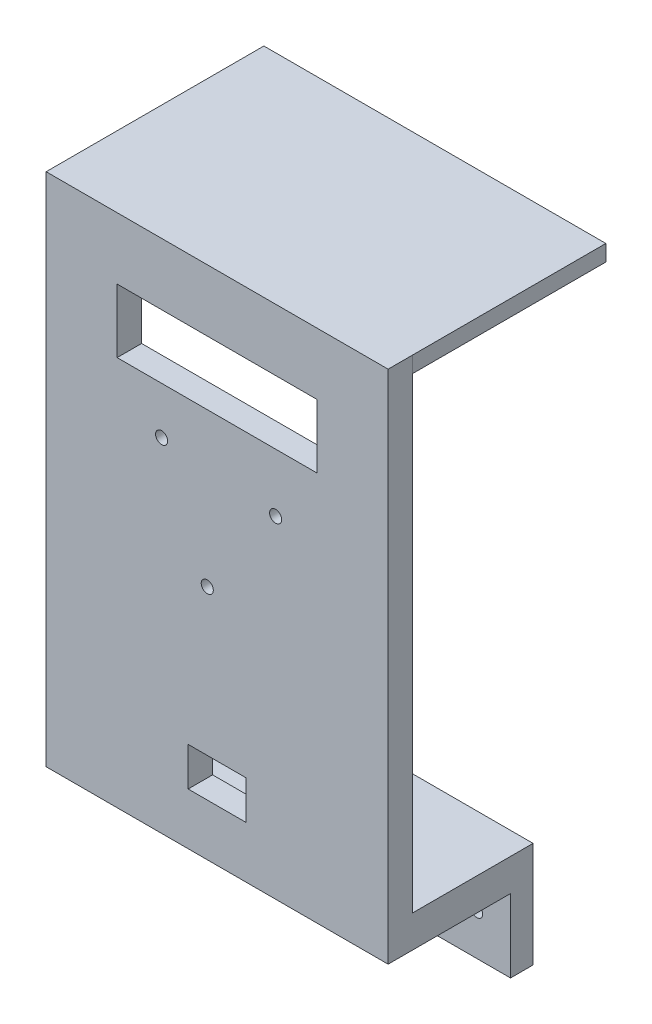
SolidWorks part; units mm, degrees
ref_plane "정면" through (0, 0, 0) normal (0, 0, 1) x (1, 0, 0)
ref_plane "윗면" through (0, 0, 0) normal (0, 1, 0) x (1, 0, 0)
ref_plane "우측면" through (0, 0, 0) normal (1, 0, 0) x (0, 0, -1)
sketch "스케치1" plane through (0, 0, 0) normal (0, 0, 1) x (1, 0, 0)
  line L0 (0, 31.6653) -> (0, -34.8319) construction
  line L1 (-49.7332, 0) -> (50.292, 0) construction
  line L3 (-49.7332, 31.7122) -> (56.4388, 31.7122)
  line L4 (-49.7332, 31.7122) -> (-49.7332, -0.9878)
  line L5 (-49.7332, -0.9878) -> (56.4388, -0.9878)
  line L6 (56.4388, 31.7122) -> (56.4388, -0.9878)
  circle A0 centre (46.0248, 11.8122) radius 1.778
  circle A1 centre (34.8488, 11.8122) radius 1.778
  circle A2 centre (-38.7332, 12.0122) radius 1.778
  circle A3 centre (-27.5332, 12.0122) radius 1.778
  dimension "D7" = 3.556
  dimension "D8" = 3.556
  dimension "D9" = 3.556
  dimension "D10" = 3.556
  dimension "D1" = 106.172
  dimension "D2" = 32.7
  dimension "D3" = 10.414
  dimension "D4" = 11.176
  dimension "D5" = 11
  dimension "D6" = 11.2
  dimension "D11" = 13
  dimension "D12" = 12.8
  dimension "D13" = 12.8
  dimension "D14" = 13
extrude "보스-돌출1" add sketch "스케치1" along normal blind 15
sketch "스케치2" plane through (0, 0, 15) normal (0, 0, 1) x (1, 0, 0)
  line L0 (56.4388, -0.9878) -> (56.4388, 31.7122) construction
  line L1 (56.4388, 31.7122) -> (-49.7332, 31.7122)
  line L2 (56.4388, 31.7122) -> (56.4388, -0.9878)
  line L3 (56.4388, -0.9878) -> (-49.7332, -0.9878)
  line L4 (-49.7332, 31.7122) -> (-49.7332, -0.9878)
  line L5 (-49.7332, 31.7122) -> (-49.7332, -0.9878) construction
  line L6 (-49.7332, -0.9878) -> (56.4388, -0.9878) construction
  circle A0 centre (-38.7332, 12.0122) radius 1.778
  circle A1 centre (-27.5332, 12.0122) radius 1.778
  circle A2 centre (34.8488, 11.8122) radius 1.778
  circle A3 centre (46.0248, 11.8122) radius 1.778
extrude "보스-돌출2" add sketch "스케치2" along normal blind 30
sketch "스케치4" plane through (-49.7332, 0, 0) normal (-1, 0, 0) x (0, 0, 1)
  line L0 (45, -0.9878) -> (25.5028, 31.7122)
  line L1 (45, 31.7122) -> (45, -0.9878) construction
  line L2 (45, 31.7122) -> (25.5028, 31.7122)
  line L3 (45, 31.7122) -> (45, -0.9878)
extrude "보스-돌출3" add sketch "스케치4" against normal blind 106
sketch "스케치6" plane through (0, 31.7122, 0) normal (0, 1, 0) x (1, 0, 0)
sketch "스케치8" plane through (0, 31.7122, 0) normal (0, 1, 0) x (1, 0, 0)
  line L0 (-49.7332, -45) -> (-49.7332, 0) construction
  line L1 (56.4388, -45) -> (-49.7332, -45)
  line L2 (56.4388, -45) -> (56.4388, -37.402)
  line L3 (56.4388, -37.402) -> (-49.7332, -37.402)
  line L4 (-49.7332, -45) -> (-49.7332, -37.402)
extrude "보스-돌출5" add sketch "스케치8" along normal blind 140
sketch "스케치9" plane through (-49.7332, 0, 0) normal (-1, 0, 0) x (0, 0, 1)
  line L0 (45, -0.9878) -> (17.0512, -0.9878)
  line L1 (17.0512, -0.9878) -> (45, 21.7218)
  line L2 (45, 171.7122) -> (45, -0.9878) construction
  line L3 (45, 21.7218) -> (45, -0.9878)
extrude "컷-돌출1" cut sketch "스케치9" against normal blind 146
sketch "스케치10" plane through (0, 0, 37.402) normal (0, 0, -1) x (-1, 0, 0)
  line L0 (49.7332, 171.7122) -> (49.7332, 31.7122) construction
  line L1 (-56.4388, 171.7122) -> (49.7332, 171.7122)
  line L2 (-56.4388, 171.7122) -> (-56.4388, 169.9692)
  line L3 (-56.4388, 169.9692) -> (49.7332, 169.9692)
  line L4 (49.7332, 171.7122) -> (49.7332, 169.9692)
sketch "스케치11" plane through (0, 171.7122, 0) normal (0, 1, 0) x (1, 0, 0)
  line L1 (56.4388, -45) -> (-49.7332, -45)
  line L2 (56.4388, -45) -> (56.4388, -37.402)
  line L3 (56.4388, -37.402) -> (-49.7332, -37.402)
  line L4 (-49.7332, -45) -> (-49.7332, -37.402)
extrude "보스-돌출7" add sketch "스케치11" along normal blind 10
sketch "스케치12" plane through (0, 0, 37.402) normal (0, 0, -1) x (-1, 0, 0)
  line L1 (49.7332, 181.7122) -> (-56.4388, 181.7122)
  line L2 (49.7332, 181.7122) -> (49.7332, 169.9692)
  line L3 (49.7332, 169.9692) -> (-56.4388, 169.9692)
  line L4 (-56.4388, 181.7122) -> (-56.4388, 169.9692)
sketch "스케치13" plane through (0, 0, 37.402) normal (0, 0, -1) x (-1, 0, 0)
  line L1 (-56.4388, 181.7122) -> (49.7332, 181.7122)
  line L2 (-56.4388, 181.7122) -> (-56.4388, 174.0177)
  line L3 (-56.4388, 174.0177) -> (49.7332, 174.0177)
  line L4 (49.7332, 181.7122) -> (49.7332, 174.0177)
sketch "스케치14" plane through (0, 0, 37.402) normal (0, 0, -1) x (-1, 0, 0)
  line L0 (-56.4388, 181.7122) -> (-56.4388, 31.7122) construction
  line L1 (49.7332, 181.7122) -> (-56.4388, 181.7122)
  line L2 (49.7332, 181.7122) -> (49.7332, 164.2058)
  line L3 (49.7332, 164.2058) -> (-56.4388, 164.2058)
  line L4 (-56.4388, 181.7122) -> (-56.4388, 164.2058)
sketch "스케치15" plane through (0, 0, 37.402) normal (0, 0, -1) x (-1, 0, 0)
  line L1 (49.7332, 181.7122) -> (-56.4377, 181.7122)
  line L2 (49.7332, 181.7122) -> (49.7332, 176.7122)
  line L3 (49.7332, 176.7122) -> (-56.4377, 176.7122)
  line L4 (-56.4377, 181.7122) -> (-56.4377, 176.7122)
  dimension "D1" = 5
extrude "보스-돌출11" add sketch "스케치15" along normal blind 60
sketch "스케치16" plane through (0, 0, 45) normal (0, 0, 1) x (1, 0, 0)
  line L0 (-49.7332, 44.5204) -> (56.4388, 44.5204) construction
  line L1 (12.3528, 49.7841) -> (-5.6472, 49.7841)
  line L2 (12.3528, 49.7841) -> (12.3528, 37.7841)
  line L3 (12.3528, 37.7841) -> (-5.6472, 37.7841)
  line L4 (-5.6472, 49.7841) -> (-5.6472, 37.7841)
  line L5 (-49.7332, 181.7122) -> (-49.7332, 21.7218) construction
  line L6 (56.4388, 21.7218) -> (56.4388, 181.7122) construction
  line L7 (3.3528, 49.7841) -> (3.3528, 37.7841) construction
  dimension "D1" = 12
  dimension "D2" = 18
extrude "컷-돌출2" cut sketch "스케치16" against normal blind 7.8
sketch "스케치18" plane through (0, 0, 45) normal (0, 0, 1) x (1, 0, 0)
  circle A1 centre (-13.8821, 128.1414) radius 1.875
  circle A3 centre (21.5155, 124.7012) radius 1.875
  circle A4 centre (0.2881, 95.1274) radius 1.875
  dimension "D2" = 3.75
  dimension "D3" = 3.75
  dimension "D4" = 3.75
extrude "컷-돌출3" cut sketch "스케치18" against normal blind 10
sketch "스케치19" plane through (0, 0, 45) normal (0, 0, 1) x (1, 0, 0)
  line L0 (3.3528, 181.7122) -> (3.3528, 49.7841) construction
  line L1 (-49.7332, 181.7122) -> (56.4388, 181.7122) construction
  line L2 (12.3528, 49.7841) -> (-5.6472, 49.7841) construction
  circle A0 centre (3.3528, 115.7481) radius 24
  dimension "D1" = 48
sketch "스케치20" plane through (0, 0, 45) normal (0, 0, 1) x (1, 0, 0)
  line L1 (56.4388, 21.7218) -> (-49.7332, 21.7218)
  line L2 (56.4388, 21.7218) -> (56.4388, -0.9878)
  line L3 (56.4388, -0.9878) -> (-49.7332, -0.9878)
  line L4 (-49.7332, 21.7218) -> (-49.7332, -0.9878)
extrude "컷-돌출4" cut sketch "스케치20" against normal blind 33
sketch "스케치21" plane through (0, 0, 12) normal (0, 0, 1) x (1, 0, 0)
  line L1 (56.4388, 21.7218) -> (-49.7332, 21.7218)
  line L2 (56.4388, 21.7218) -> (56.4388, -0.9878)
  line L3 (56.4388, -0.9878) -> (-49.7332, -0.9878)
  line L4 (-49.7332, 21.7218) -> (-49.7332, -0.9878)
extrude "컷-돌출5" cut sketch "스케치21" against normal blind 5
sketch "스케치22" plane through (0, -0.9878, 0) normal (0, -1, 0) x (1, 0, 0)
  line L1 (-49.7332, 7) -> (56.4388, 7)
  line L2 (-49.7332, 7) -> (-49.7332, 0)
  line L3 (-49.7332, 0) -> (56.4388, 0)
  line L4 (56.4388, 7) -> (56.4388, 0)
sketch "스케치23" plane through (-49.7332, 0, 0) normal (-1, 0, 0) x (0, 0, 1)
  line L0 (45, 163.7523) -> (45, 199.0827)
  line L1 (45, 181.7122) -> (45, 21.7218) construction
  line L2 (45, 199.0827) -> (37.402, 199.0827)
  line L3 (37.402, 199.0827) -> (37.402, 163.7523)
  line L4 (37.402, 176.7122) -> (37.402, 31.7122) construction
  line L5 (45, 163.7523) -> (37.402, 163.7523)
sketch "스케치24" plane through (0, 0, 37.402) normal (0, 0, -1) x (-1, 0, 0)
  line L1 (49.7332, 163.7523) -> (54.7332, 163.7523)
  line L2 (49.7332, 163.7523) -> (49.7332, 199.0827)
  line L3 (49.7332, 199.0827) -> (54.7332, 199.0827)
  line L4 (54.7332, 163.7523) -> (54.7332, 199.0827)
sketch "스케치26" plane through (-54.7332, 0, 0) normal (-1, 0, 0) x (0, 0, 1)
  line L1 (1.902, 199.0827) -> (4.5302, 199.0827)
  line L2 (1.902, 199.0827) -> (1.902, 176.6973)
  line L3 (1.902, 176.6973) -> (4.5302, 176.6973)
  line L4 (4.5302, 199.0827) -> (4.5302, 176.6973)
sketch "스케치27" plane through (0, 0, 37.402) normal (0, 0, -1) x (-1, 0, 0)
  line L0 (5.6472, 37.7841) -> (-12.3528, 37.7841) construction
  line L1 (-9.0528, 37.7841) -> (-2.3528, 37.7841)
  line L2 (-9.0528, 37.7841) -> (-9.0528, 36.908)
  line L3 (-9.0528, 36.908) -> (-2.3528, 36.908)
  line L4 (-2.3528, 37.7841) -> (-2.3528, 36.908)
  line L5 (-12.3528, 37.7841) -> (-12.3528, 49.7841) construction
  dimension "D1" = 3.3
  dimension "D2" = 6.7
sketch "스케치28" plane through (0, 37.7841, 0) normal (0, 1, 0) x (1, 0, 0)
  line L0 (9.0528, -33.402) -> (9.0528, -37.402) construction
  line L1 (2.3528, -33.402) -> (9.0528, -33.402)
  line L2 (2.3528, -33.402) -> (2.3528, -34.0141)
  line L3 (2.3528, -34.0141) -> (9.0528, -34.0141)
  line L4 (9.0528, -33.402) -> (9.0528, -34.0141)
sketch "스케치29" plane through (0, 0, 37.402) normal (0, 0, -1) x (-1, 0, 0)
  line L0 (-12.3528, 49.7841) -> (5.6472, 49.7841) construction
  line L1 (-9.3528, 49.7841) -> (-2.6528, 49.7841)
  line L2 (-9.3528, 49.7841) -> (-9.3528, 49.8649)
  line L3 (-9.3528, 49.8649) -> (-2.6528, 49.8649)
  line L4 (-2.6528, 49.7841) -> (-2.6528, 49.8649)
  line L5 (-12.3528, 37.7841) -> (-12.3528, 49.7841) construction
  dimension "D1" = 3
  dimension "D2" = 6.7
sketch "스케치30" plane through (0, 0, 45) normal (0, 0, 1) x (1, 0, 0)
  line L0 (-49.7332, 181.7122) -> (56.4388, 181.7122) construction
  line L1 (34.4002, 142.7471) -> (-27.6946, 142.7471)
  line L2 (34.4002, 142.7471) -> (34.4002, 162.5257)
  line L3 (34.4002, 162.5257) -> (-27.6946, 162.5257)
  line L4 (-27.6946, 142.7471) -> (-27.6946, 162.5257)
  line L6 (3.3528, 142.7471) -> (3.3528, 181.7122) construction
extrude "컷-돌출6" cut sketch "스케치30" against normal blind 10
